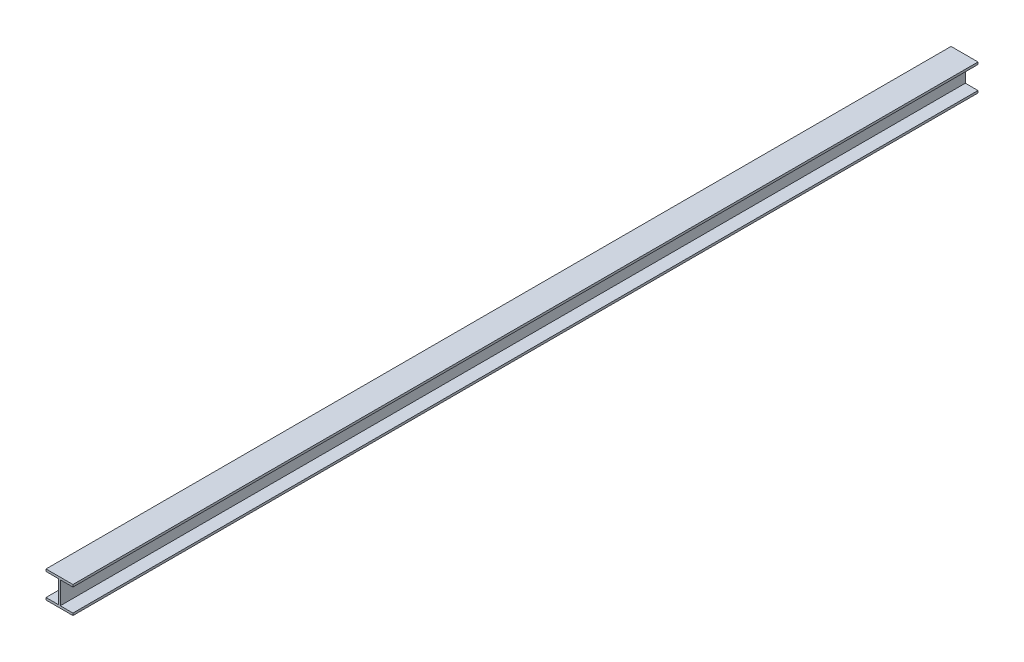
SolidWorks part; units mm, degrees
ref_plane "Front Plane" through (0, 0, 0) normal (0, 0, 1) x (1, 0, 0)
ref_plane "Top Plane" through (0, 0, 0) normal (0, 1, 0) x (1, 0, 0)
ref_plane "Right Plane" through (0, 0, 0) normal (1, 0, 0) x (0, 0, -1)
sketch "Sketch1" plane through (0, 0, 0) normal (0, 0, 1) x (1, 0, 0)
  line L0 (0, 0) -> (127, 0)
  line L1 (127, 0) -> (127, 10.4648)
  line L2 (127, 10.4648) -> (67.4751, 10.4648)
  line L3 (67.4751, 10.4648) -> (67.4751, 116.5352)
  line L4 (67.4751, 116.5352) -> (127, 116.5352)
  line L5 (127, 116.5352) -> (127, 127)
  line L6 (127, 127) -> (0, 127)
  line L7 (0, 127) -> (0, 116.5352)
  line L8 (0, 116.5352) -> (59.5249, 116.5352)
  line L9 (59.5249, 116.5352) -> (59.5249, 10.4648)
  line L10 (59.5249, 10.4648) -> (0, 10.4648)
  line L11 (0, 10.4648) -> (0, 0)
  dimension "D1" = 127
  dimension "D2" = 127
  dimension "D3" = 127
  dimension "D4" = 10.4648
  dimension "D5" = 10.4648
  dimension "D6" = 10.4648
  dimension "D7" = 10.4648
  dimension "D8" = 7.9502
  dimension "D9" = 59.5249
extrude "Boss-Extrude1" add sketch "Sketch1" along normal blind 4267.2
